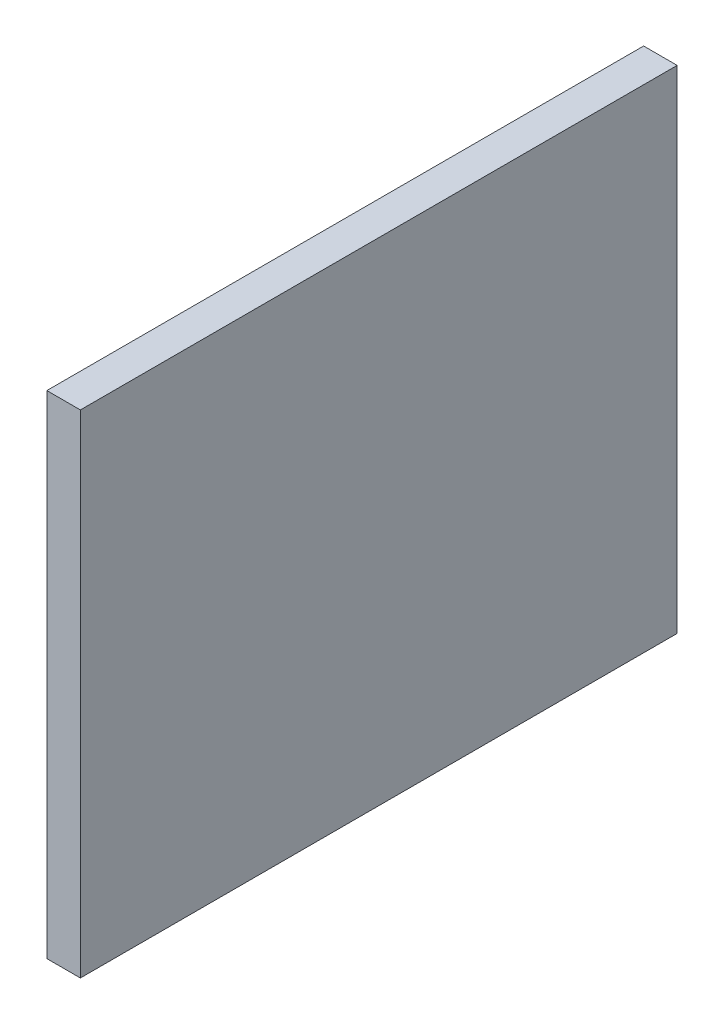
SolidWorks part; units mm, degrees
ref_plane "Front" through (0, 0, 0) normal (0, 0, 1) x (1, 0, 0)
ref_plane "Top" through (0, 0, 0) normal (0, 1, 0) x (1, 0, 0)
ref_plane "Right" through (0, 0, 0) normal (1, 0, 0) x (0, 0, -1)
sketch "Sketch1" plane through (0, 0, 0) normal (0, 1, 0) x (1, 0, 0)
  line L1 (0, 0) -> (76.2, 0)
  line L2 (0, 0) -> (0, -1355.725)
  line L3 (0, -1355.725) -> (76.2, -1355.725)
  line L4 (76.2, 0) -> (76.2, -1355.725)
  dimension "D1" = 76.2
  dimension "D2" = 1355.725
extrude "Boss-Extrude1" add sketch "Sketch1" along normal blind 1117.6
sketch "Sketch2" plane through (0, 0, 0) normal (-1, 0, 0) x (0, 0, 1)
  line L0 (0, 1117.6) -> (1355.725, 1117.6) construction
  line L1 (1355.725, 0) -> (1254.125, 0)
  line L2 (1355.725, 0) -> (1355.725, 1117.6)
  line L3 (1355.725, 1117.6) -> (1254.125, 1117.6)
  line L4 (1254.125, 0) -> (1254.125, 1117.6)
  dimension "D1" = 101.6
extrude "Cut-Extrude1" [suppressed] cut sketch "Sketch2" against normal through all
sketch "Sketch3" [suppressed] plane through (0, 0, 0) normal (-1, 0, 0) x (0, 0, 1)
  line L0 (0, 1016) -> (1355.725, 1016) construction
  line L1 (1355.725, 0) -> (1301.75, 0)
  line L2 (1355.725, 0) -> (1355.725, 1016)
  line L3 (1355.725, 1016) -> (1301.75, 1016)
  line L4 (1301.75, 0) -> (1301.75, 1016)
  line L5 (0, 1016) -> (0, 0) construction
  dimension "D1" = 1301.75
extrude "Cut-Extrude2" [suppressed] cut sketch "Sketch3" against normal through all
